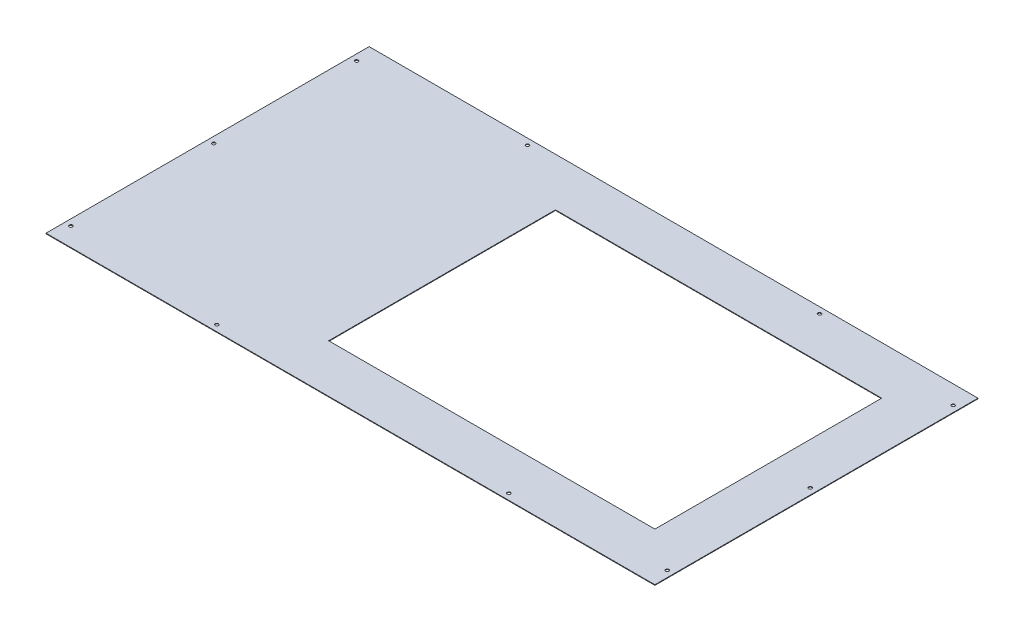
SolidWorks part; units mm, degrees
material "1023 Carbon Steel Sheet (SS)"
ref_plane "Front Plane" through (0, 0, 0) normal (0, 0, 1) x (1, 0, 0)
ref_plane "Top Plane" through (0, 0, 0) normal (0, 1, 0) x (1, 0, 0)
ref_plane "Right Plane" through (0, 0, 0) normal (1, 0, 0) x (0, 0, -1)
sketch "Sketch1" plane through (0, 0, 0) normal (0, 1, 0) x (1, 0, 0)
  line L1 (-502.0402, 180.7666) -> (164.7098, 180.7666)
  line L2 (-502.0402, 180.7666) -> (-502.0402, -282.7834)
  line L3 (-502.0402, -282.7834) -> (164.7098, -282.7834)
  line L4 (164.7098, 180.7666) -> (164.7098, -282.7834)
  line L5 (-981.4652, 279.1916) -> (263.1348, 279.1916)
  line L6 (-981.4652, 279.1916) -> (-981.4652, -381.2084)
  line L7 (-981.4652, -381.2084) -> (263.1348, -381.2084)
  line L8 (263.1348, 279.1916) -> (263.1348, -381.2084)
  dimension "D1" = 463.55
  dimension "D2" = 666.75
  dimension "D3" = 98.425
  dimension "D4" = 98.425
  dimension "D5" = 98.425
  dimension "D6" = 479.425
extrude "Boss-Extrude1" add sketch "Sketch1" along normal blind 1.2192
sketch "Sketch2" plane through (0, 0, 0) normal (0, -1, 0) x (1, 0, 0)
  line L0 (263.1348, -279.1916) -> (-981.4652, -279.1916) construction
  line L1 (-968.7652, -266.4916) -> (250.4348, -266.4916) construction
  line L2 (-968.7652, -266.4916) -> (-968.7652, 368.5084) construction
  line L3 (-968.7652, 368.5084) -> (250.4348, 368.5084) construction
  line L4 (250.4348, -266.4916) -> (250.4348, 368.5084) construction
  line L5 (-981.4652, -279.1916) -> (-981.4652, 381.2084) construction
  line L6 (-981.4652, 381.2084) -> (263.1348, 381.2084) construction
  line L7 (263.1348, 381.2084) -> (263.1348, -279.1916) construction
  point P12 (-968.7652, -241.0916)
  point P13 (-968.7652, 51.0084)
  point P14 (-968.7652, 343.1084)
  point P15 (250.4348, -241.0916)
  point P16 (250.4348, 343.1084)
  point P17 (250.4348, 51.0084)
  point P18 (-644.9152, -266.4916)
  point P19 (-48.0152, -266.4916)
  point P20 (-48.0152, 368.5084)
  point P21 (-644.9152, 368.5084)
  dimension "D1" = 12.7
  dimension "D2" = 12.7
  dimension "D3" = 12.7
  dimension "D4" = 12.7
  dimension "D5" = 25.4
  dimension "D6" = 25.4
  dimension "D7" = 25.4
  dimension "D8" = 25.4
  dimension "D9" = 298.45
  dimension "D10" = 298.45
  dimension "D11" = 596.9
  dimension "D12" = 596.9
hole_wizard "1/4 Clearance Hole1" positions "Sketch4" profile "Sketch3" hole size "1/4" standard "ANSI Inch" end condition through all
sketch "Sketch4" plane through (0, 0, 0) normal (0, -1, 0) x (-1, 0, 0)
  point P0 (968.7652, 241.0916)
  point P3 (968.7652, -51.0084)
  point P6 (968.7652, -343.1084)
  point P9 (644.9152, -368.5084)
  point P12 (644.9152, 266.4916)
  point P15 (48.0152, 266.4916)
  point P18 (-250.4348, 241.0916)
  point P21 (-250.4348, -51.0084)
  point P24 (-250.4348, -343.1084)
  point P27 (48.0152, -368.5084)
sketch "Sketch3" plane through (-968.7652, 0, -241.0916) normal (1, 0, 0) x (0, 0, -1)
  line L0 (0, 0) -> (0, 1.2192)
  line L1 (0, 1.2192) -> (3.3782, 1.2192)
  line L2 (3.3782, 1.2192) -> (3.3782, 0)
  line L5 (3.3782, 0) -> (0, 0)
  line L11 (0, -6.35) -> (0, 107.95) construction
  dimension "Thru Hole Dia." = 6.7564
  dimension "Thru Hole Depth" = 1.2192
equation "\"d1\"=0.5"
equation "\"D1@Sketch2\"=\"d1\""
equation "\"D2@Sketch2\"=\"d1\""
equation "\"D3@Sketch2\"=\"d1\""
equation "\"D4@Sketch2\"=\"d1\""
